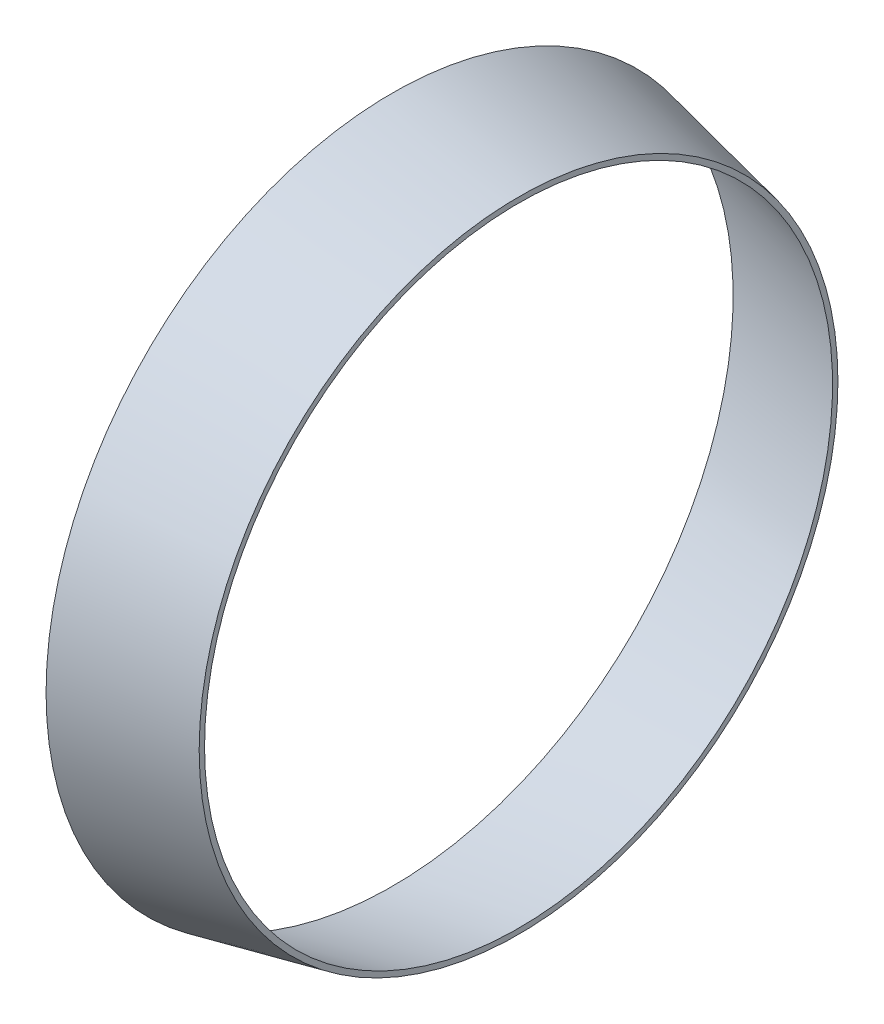
SolidWorks part; units mm, degrees
material "AISI 316 Stainless Steel Sheet (SS)"
ref_plane "Front Plane" through (0, 0, 0) normal (0, 0, 1) x (1, 0, 0)
ref_plane "Top Plane" through (0, 0, 0) normal (0, 1, 0) x (1, 0, 0)
ref_plane "Right Plane" through (0, 0, 0) normal (1, 0, 0) x (0, 0, -1)
sketch "Sketch2" plane through (0, 0, 0) normal (0, 0, 1) x (1, 0, 0)
  line L0 (0, 0) -> (58922.4238, 0) construction
  line L1 (1.5723, 79.5) -> (58923.9961, 79.5) construction
  line L2 (0, 64.5) -> (0, 63.5)
  line L3 (0, 63.5) -> (23.5232, 58.5)
  line L4 (23.5232, 58.5) -> (23.5232, 59.5)
  line L5 (23.5232, 59.5) -> (0, 64.5)
  line L6 (0, 64.5) -> (4.4997, 64.5) construction
  dimension "D1" = 79.5
  dimension "D2" = 15
  dimension "D3" = 1
  dimension "D4" = 1
  dimension "D5" = 12
  dimension "D6" = 20
  dimension "D7" = 63.5
  dimension "D8" = 23.5232
  dimension "D9" = 58.5
revolve "Revolve1" add sketch "Sketch2" angle 360 about L0
sketch "Sketch3" plane through (23.5232, 0, 0) normal (1, 0, 0) x (0, 0, -1)
  line L1 (1.328, 69.3356) -> (2.328, 69.3356)
  line L2 (1.328, 69.3356) -> (1.328, 60.3356)
  line L3 (1.328, 60.3356) -> (2.328, 60.3356)
  line L4 (2.328, 69.3356) -> (2.328, 60.3356)
  dimension "D1" = 1
  dimension "D2" = 9
sketch "Sketch7" plane through (23.5232, 0, 0) normal (1, 0, 0) x (0, 0, -1)
  circle A0 centre (0, 0) radius 59
  dimension "D1" = 118
sketch "Sketch9" plane through (0, 0, 0) normal (0, 0, 1) x (1, 0, 0)
  line L0 (0, 0) -> (50000, 0) construction
